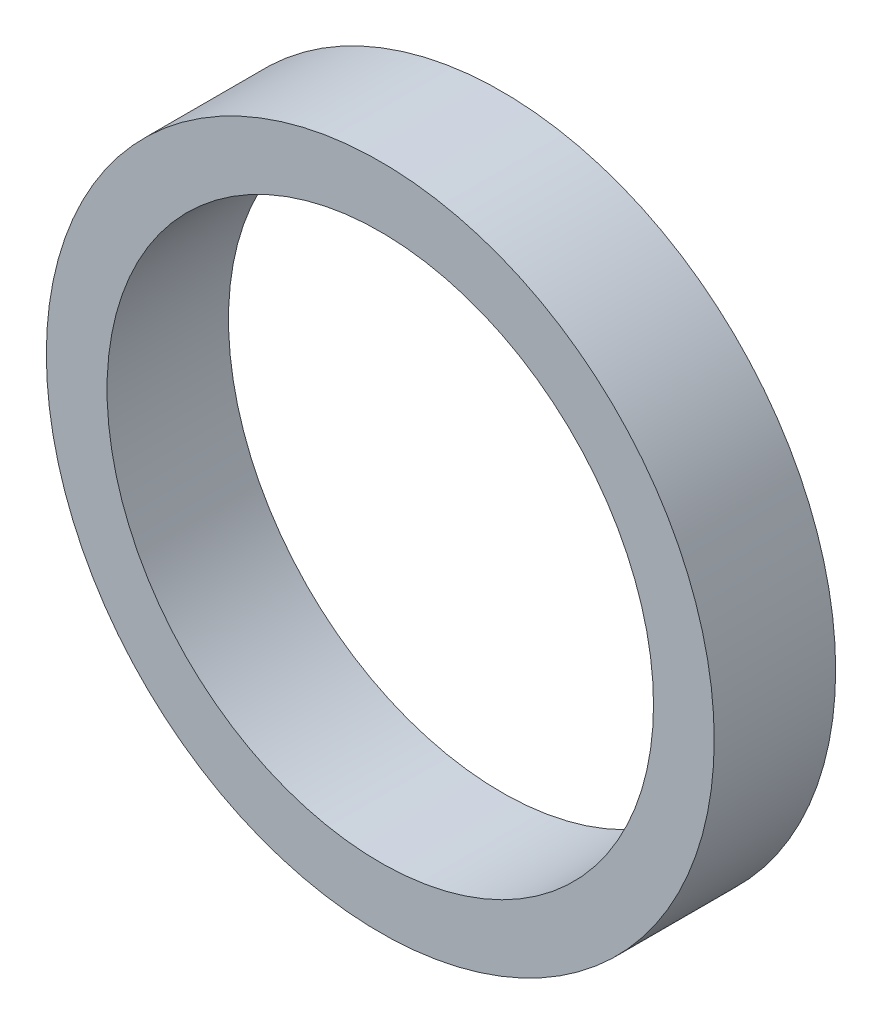
SolidWorks part; units mm, degrees
ref_plane "Front Plane" through (0, 0, 0) normal (0, 0, 1) x (1, 0, 0)
ref_plane "Top Plane" through (0, 0, 0) normal (0, 1, 0) x (1, 0, 0)
ref_plane "Right Plane" through (0, 0, 0) normal (1, 0, 0) x (0, 0, -1)
sketch "Sketch1" plane through (0, 0, 0) normal (0, 0, 1) x (1, 0, 0)
  line L0 (69.85, 0) -> (57.15, 0) construction
  line L1 (-69.85, 0) -> (69.85, 0) construction
  dimension "OD" = 139.7
  dimension "Wall Thickness" = 12.7
sketch "Sketch2" plane through (0, 0, 0) normal (1, 0, 0) x (0, 0, -1)
  line L0 (12.7, 0) -> (-12.7, 0)
  point P4 (0, 0)
  dimension "Length" = 25.4
sketch "Sketch3" plane through (0, 0, 0) normal (0, 0, 1) x (1, 0, 0)
  circle A0 centre (0, 0) radius 69.85
  circle A1 centre (0, 0) radius 57.15
extrude "Boss-Extrude1" add sketch "Sketch3" along normal up to vertex (12.7 mm away) and the other way up to vertex (12.7 mm away) up to point (0, 0, 12.7) other way up to point (0, 0, -12.7)
